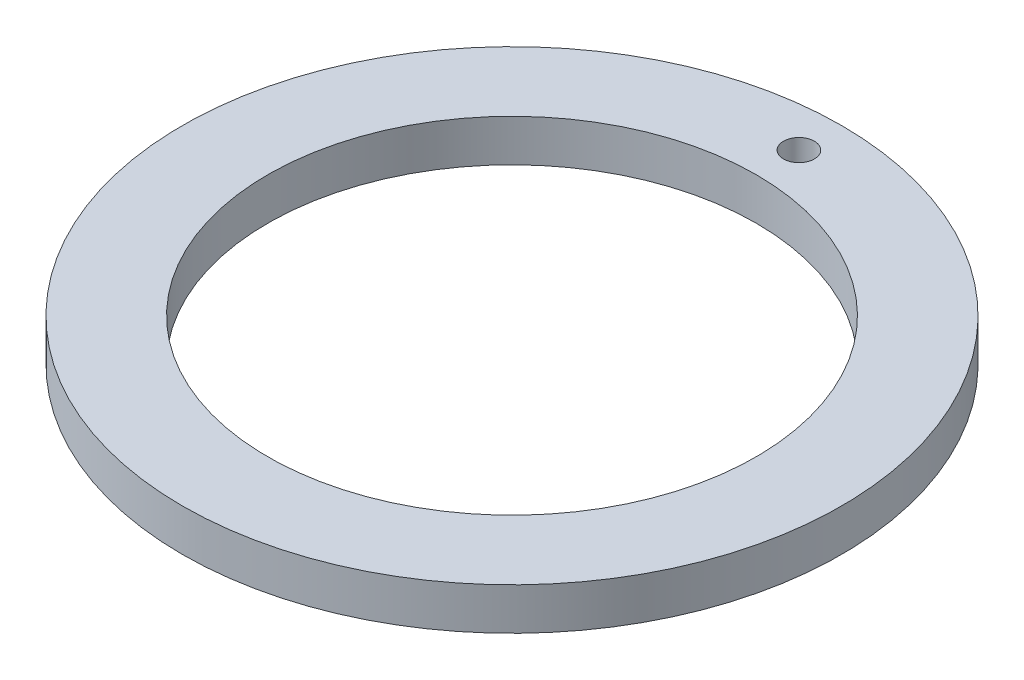
SolidWorks part; units mm, degrees
ref_plane "Front Plane" through (0, 0, 0) normal (0, 0, 1) x (1, 0, 0)
ref_plane "Top Plane" through (0, 0, 0) normal (0, 1, 0) x (1, 0, 0)
ref_plane "Right Plane" through (0, 0, 0) normal (1, 0, 0) x (0, 0, -1)
sketch "Sketch1" plane through (0, 0, 0) normal (0, 1, 0) x (1, 0, 0)
  circle A0 centre (0, 0) radius 50.8
  circle A1 centre (0, 0) radius 39.37
  dimension "D1" = 101.6
  dimension "D2" = 78.74
extrude "Boss-Extrude1" add sketch "Sketch1" along normal blind 6.477 contours A0
sketch "Sketch3" plane through (0, 0, 0) normal (0, -1, 0) x (-1, 0, 0)
  circle A0 centre (0, 0) radius 37.6555
  dimension "D1" = 75.311
extrude "Cut-Extrude1" cut sketch "Sketch3" against normal blind 6.477
sketch "Sketch4" plane through (0, 0, 0) normal (0, -1, 0) x (1, 0, 0)
  line L0 (0, -37.6555) -> (0, -50.8) construction
  circle A0 centre (0, 0) radius 37.6555 construction
  circle A1 centre (0, 0) radius 50.8 construction
  circle A2 centre (0, -44.2277) radius 2.3812
  dimension "D1" = 4.7625
extrude "Cut-Extrude2" cut sketch "Sketch4" against normal blind 6.477
